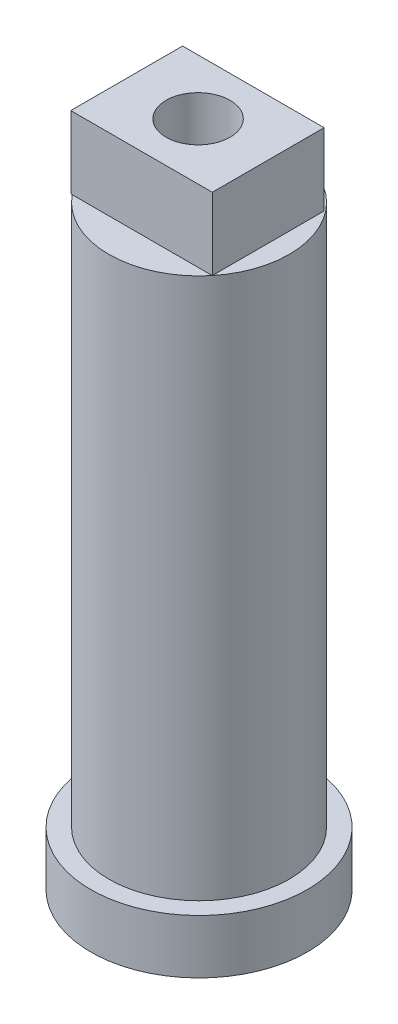
SolidWorks part; units mm, degrees
ref_plane "Front Plane" through (0, 0, 0) normal (0, 0, 1) x (1, 0, 0)
ref_plane "Top Plane" through (0, 0, 0) normal (0, 1, 0) x (1, 0, 0)
ref_plane "Right Plane" through (0, 0, 0) normal (1, 0, 0) x (0, 0, -1)
sketch "Sketch1" plane through (0, 0, 0) normal (0, 1, 0) x (1, 0, 0)
  circle A0 centre (-2.3765, 3.6967) radius 5
extrude "Boss-Extrude2" add sketch "Sketch1" along normal blind 30
sketch "Sketch2" plane through (0, 30, 0) normal (0, 1, 0) x (1, 0, 0)
  line L1 (-6.3389, 6.7462) -> (1.5064, 6.7462)
  line L2 (-6.3389, 6.7462) -> (-6.3389, 0.5466)
  line L3 (-6.3389, 0.5466) -> (1.5064, 0.5466)
  line L4 (1.5064, 6.7462) -> (1.5064, 0.5466)
  circle A0 centre (-2.3765, 3.6967) radius 5 construction
extrude "Boss-Extrude3" add sketch "Sketch2" along normal blind 4
sketch "Sketch3" plane through (0, 34, 0) normal (0, 1, 0) x (1, 0, 0)
  circle A0 centre (-2.4155, 3.6812) radius 1.7747
extrude "Cut-Extrude1" cut sketch "Sketch3" against normal blind 3
sketch "Sketch4" plane through (0, 0, 0) normal (0, -1, 0) x (-1, 0, 0)
  circle A0 centre (2.3765, 3.6967) radius 6
  dimension "D1" = 12
extrude "Boss-Extrude4" add sketch "Sketch4" along normal blind 3
